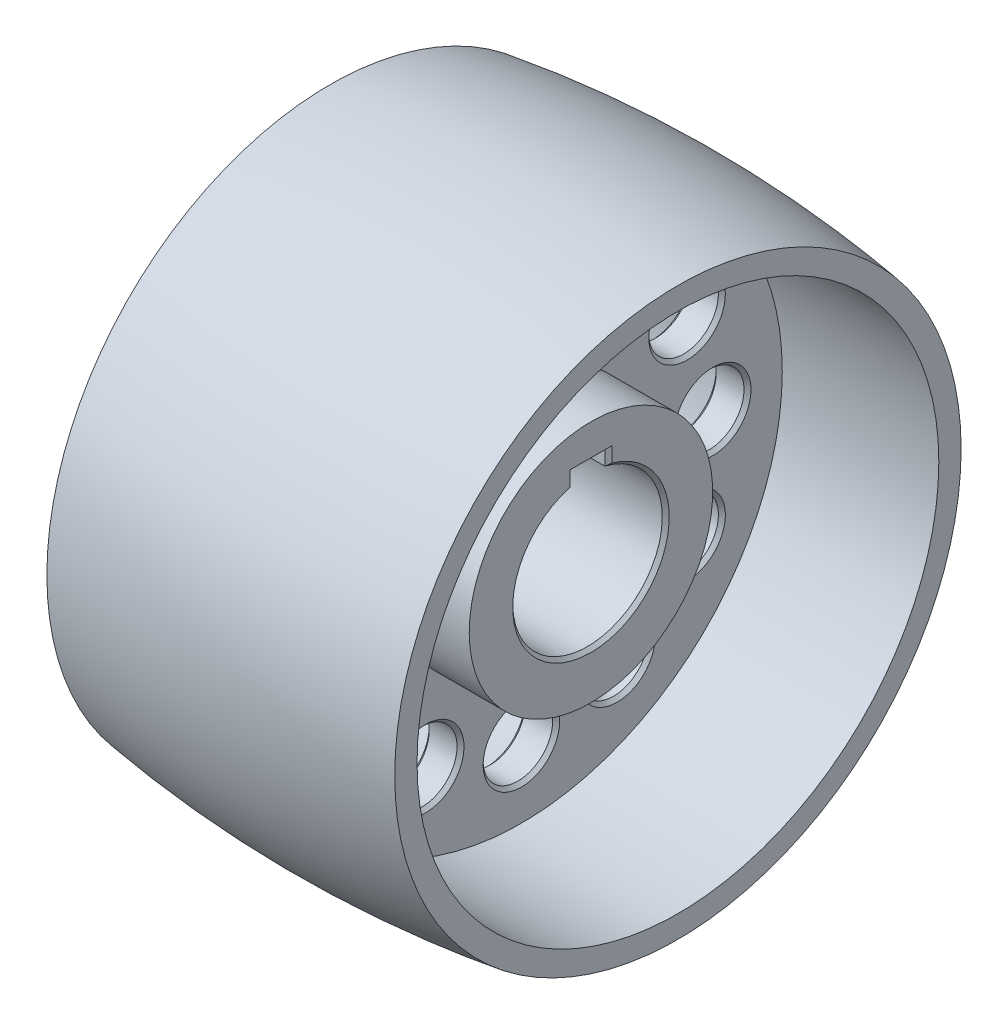
SolidWorks part; units mm, degrees
ref_plane "Płaszczyzna przednia" through (0, 0, 0) normal (0, 0, 1) x (1, 0, 0)
ref_plane "Płaszczyzna górna" through (0, 0, 0) normal (0, 1, 0) x (1, 0, 0)
ref_plane "Płaszczyzna prawa" through (0, 0, 0) normal (1, 0, 0) x (0, 0, -1)
sketch "Szkic1" plane through (0, 0, 0) normal (0, 0, 1) x (1, 0, 0)
  line L0 (0, 170) -> (0, -170) construction
  line L1 (-100, 0) -> (100, 0) construction
  line L2 (-10, 70) -> (-10, 150)
  line L3 (-50, 0) -> (50, 0)
  line L4 (-50, 0) -> (-50, 70)
  line L5 (-50, 70) -> (-10, 70)
  line L6 (50, 0) -> (50, 70)
  line L7 (-10, 150) -> (-100, 150)
  line L8 (-100, 150) -> (-100, 162.8203)
  line L9 (10, 70) -> (10, 150)
  line L10 (10, 150) -> (100, 150)
  line L11 (100, 150) -> (100, 162.8203)
  line L12 (10, 70) -> (50, 70)
  arc A0 (-100, 162.8203) -> (100, 162.8203) centre (0, -530) cw
  dimension "D3" = 700
  dimension "D1" = 340
  dimension "D2" = 200
  dimension "D4" = 70
  dimension "D5" = 100
  dimension "D6" = 80
  dimension "D7" = 20
  dimension "D8" = 200
revolve "Obrót1" add sketch "Szkic1" angle 360 about L3
sketch "Szkic2" plane through (-50, 0, 0) normal (-1, 0, 0) x (0, 0, 1)
  line L0 (-10, 50) -> (10, 50)
  line L1 (-10, 50) -> (-10, 41.821)
  line L2 (10, 50) -> (10, 41.821)
  line L3 (0, 0) -> (0, 50) construction
  circle A0 centre (0, 0) radius 43
  dimension "D1" = 86
  dimension "D2" = 20
  dimension "D3" = 93
extrude "Wytnij-wyciągnięcie1" cut sketch "Szkic2" against normal up to next
chamfer "Sfazowanie1" distance 2 angle 45 8 edges at (50, -43, 0) (50, 45.9105, 10) (50, 45.9105, -10) (50, 50, 0) (-50, 45.9105, 10) (-50, 50, 0) (-50, 45.9105, -10) (-50, -43, 0)
sketch "Szkic3" plane through (-10, 0, 0) normal (-1, 0, 0) x (0, 0, 1)
  line L0 (0, 0) -> (0, 110) construction
  circle A0 centre (0, 110) radius 20
  dimension "D2" = 40
  dimension "D1" = 110
extrude "Wytnij-wyciągnięcie2" cut sketch "Szkic3" against normal up to next
chamfer "Sfazowanie2" distance 2 angle 45 2 edges at (10, 110, 20) (-10, 110, 20)
sketch "Szkic4" plane through (0, 0, 0) normal (0, 0, 1) x (1, 0, 0)
  line L0 (-100, 0) -> (100, 0) construction
  line L1 (-100, 162.8203) -> (-100, -162.8203) construction
  line L2 (100, -162.8203) -> (100, 162.8203) construction
pattern_circular "Szyk kołowy1" count 12 over 360 about axis through (0, 0, 0) along (1, 0, 0) of "Wytnij-wyciągnięcie2", "Sfazowanie2"
